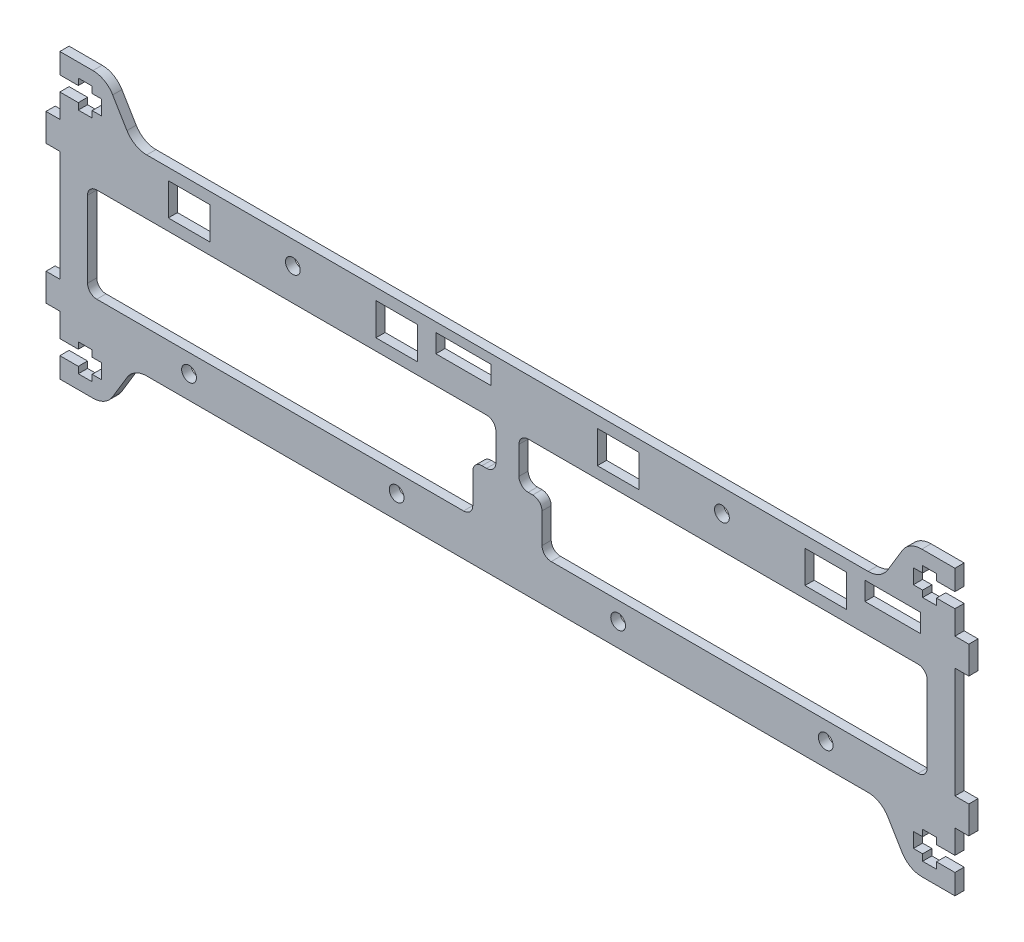
SolidWorks part; units mm, degrees
material "Thornel Mat VMA"
ref_plane "前视基准面" through (0, 0, 0) normal (0, 0, 1) x (1, 0, 0)
ref_plane "上视基准面" through (0, 0, 0) normal (0, 1, 0) x (1, 0, 0)
ref_plane "右视基准面" through (0, 0, 0) normal (1, 0, 0) x (0, 0, -1)
sketch "草图1" plane through (0, 0, 0) normal (0, 0, 1) x (1, 0, 0)
  line L0 (0, 37.9064) -> (0, -47.7397) construction
  line L5 (-108.9606, 0) -> (106.7668, 0) construction
  line L6 (-46.5, 17.25) -> (-46.5, -19.8871) construction
  line L57 (-91, 10.25) -> (-7.5, 10.25)
  line L58 (-91, 10.25) -> (-91, -10.25)
  line L59 (-91, -10.25) -> (-7.5, -10.25)
  line L60 (-7.5, 10.25) -> (-7.5, -10.25)
  line L61 (7.5, 10.25) -> (91, 10.25)
  line L62 (7.5, 10.25) -> (7.5, -10.25)
  line L63 (7.5, -10.25) -> (91, -10.25)
  line L64 (91, 10.25) -> (91, -10.25)
  line L80 (64, -19.25) -> (29, -19.25)
  line L81 (-97, 22.25) -> (97, 22.25)
  line L82 (-97, 22.25) -> (-97, -24.75)
  line L83 (-97, -24.75) -> (-64, -24.75)
  line L84 (97, 22.25) -> (97, -24.75)
  line L86 (-64, -24.75) -> (-64, -19.25)
  line L87 (-64, -19.25) -> (-29, -19.25)
  line L88 (-29, -24.75) -> (-29, -19.25)
  line L89 (29, -24.75) -> (29, -19.25)
  line L91 (64, -24.75) -> (64, -19.25)
  line L92 (-29, -24.75) -> (29, -24.75)
  line L93 (64, -24.75) -> (97, -24.75)
  circle A0 centre (-46.5, 17.25) radius 1.6
  circle A1 centre (-69, -14.25) radius 1.6
  circle A2 centre (-24, -14.25) radius 1.6
  circle A3 centre (69, -14.25) radius 1.6
  circle A4 centre (46.5, 17.25) radius 1.6
  circle A5 centre (24, -14.25) radius 1.6
  circle A6 centre (-69, -21.75) radius 1.6
  circle A7 centre (-24, -21.75) radius 1.6
  circle A8 centre (24, -21.75) radius 1.6
  circle A9 centre (69, -21.75) radius 1.6
  point P30 (0, 0)
  dimension "D1" = 3.2
  dimension "D2" = 45
  dimension "D3" = 31.5
  dimension "D4" = 5
  dimension "D5" = 28
  dimension "D8" = 7.5
  dimension "D6" = 48
  dimension "D7" = 7
  dimension "D9" = 3
  dimension "D10" = 6
  dimension "D11" = 9
  dimension "D12" = 5
  dimension "D15" = 4
  dimension "D16" = 15
extrude "凸台-拉伸1" add sketch "草图1" along normal blind 2
sketch "草图3" plane through (0, 0, 2) normal (0, 0, 1) x (1, 0, 0)
  line L1 (-7.5, 10.25) -> (-2.5, 10.25)
  line L2 (-7.5, 10.25) -> (-7.5, 0.25)
  line L3 (-7.5, 0.25) -> (-2.5, 0.25)
  line L4 (-2.5, 10.25) -> (-2.5, 0.25)
  line L5 (7.5, 10.25) -> (2.5, 10.25)
  line L6 (7.5, 10.25) -> (7.5, 0.25)
  line L7 (7.5, 0.25) -> (2.5, 0.25)
  line L8 (2.5, 10.25) -> (2.5, 0.25)
  dimension "D1" = 5
  dimension "D2" = 10
extrude "切除-拉伸2" cut sketch "草图3" against normal through all
sketch "草图4" plane through (0, 0, 0) normal (0, 0, -1) x (-1, 0, 0)
  line L0 (-97, 22.25) -> (97, 22.25) construction
  line L1 (-73.5, 19.75) -> (-64.5, 19.75)
  line L2 (-73.5, 19.75) -> (-73.5, 12.75)
  line L3 (-73.5, 12.75) -> (-64.5, 12.75)
  line L4 (-64.5, 19.75) -> (-64.5, 12.75)
  line L5 (0, 22.25) -> (0, -24.75) construction
  line L6 (-28.5, 19.75) -> (-19.5, 19.75)
  line L7 (-28.5, 19.75) -> (-28.5, 12.75)
  line L8 (-28.5, 12.75) -> (-19.5, 12.75)
  line L9 (-19.5, 19.75) -> (-19.5, 12.75)
  line L10 (29, -24.75) -> (-29, -24.75) construction
  line L11 (-46.5, 17.25) -> (-46.5, -22.9555) construction
  line L12 (28.5, 12.75) -> (19.5, 12.75)
  line L13 (19.5, 19.75) -> (19.5, 12.75)
  line L14 (28.5, 19.75) -> (19.5, 19.75)
  line L15 (28.5, 19.75) -> (28.5, 12.75)
  line L16 (73.5, 12.75) -> (64.5, 12.75)
  line L17 (64.5, 19.75) -> (64.5, 12.75)
  line L18 (73.5, 19.75) -> (64.5, 19.75)
  line L19 (73.5, 19.75) -> (73.5, 12.75)
  line L20 (-64, -24.75) -> (-97, -24.75) construction
  line L21 (-74, -24.75) -> (-97, -24.75)
  line L22 (-74, -24.75) -> (-74, -19.25)
  line L23 (-74, -19.25) -> (-97, -19.25)
  line L24 (-97, -24.75) -> (-97, -19.25)
  line L25 (-97, -24.75) -> (-97, 22.25) construction
  line L26 (97, -24.75) -> (64, -24.75) construction
  line L27 (74, -24.75) -> (97, -24.75)
  line L28 (74, -24.75) -> (74, -19.25)
  line L29 (74, -19.25) -> (97, -19.25)
  line L30 (97, -24.75) -> (97, -19.25)
  line L31 (97, 22.25) -> (97, -24.75) construction
  line L32 (-29, -19.25) -> (-64, -19.25) construction
  line L34 (-19, -24.75) -> (19, -24.75)
  line L35 (-19, -24.75) -> (-19, -19.25)
  line L36 (-19, -19.25) -> (19, -19.25)
  line L37 (19, -24.75) -> (19, -19.25)
  circle A0 centre (-46.5, 17.25) radius 1.6 construction
  circle A1 centre (-69, -21.75) radius 1.6 construction
  circle A2 centre (-24, -21.75) radius 1.6 construction
  dimension "D1" = 4.5
  dimension "D2" = 18
  dimension "D3" = 27
  dimension "D4" = 7
  dimension "D5" = 5
  dimension "D6" = 5
extrude "切除-拉伸3" cut sketch "草图4" against normal through all
sketch "草图5" plane through (0, 0, 0) normal (0, 0, -1) x (-1, 0, 0)
  line L0 (-97, 22.25) -> (97, 22.25) construction
  line L1 (-89.5, 20.25) -> (-77.5, 20.25)
  line L2 (-89.5, 20.25) -> (-89.5, 16.25)
  line L3 (-89.5, 16.25) -> (-77.5, 16.25)
  line L4 (-77.5, 20.25) -> (-77.5, 16.25)
  line L5 (3.5, 20.25) -> (15.5, 20.25)
  line L6 (3.5, 20.25) -> (3.5, 16.25)
  line L7 (3.5, 16.25) -> (15.5, 16.25)
  line L8 (15.5, 20.25) -> (15.5, 16.25)
  line L9 (-73.5, 19.75) -> (-73.5, 12.75) construction
  line L10 (19.5, 19.75) -> (19.5, 12.75) construction
  point P12 (16.5382, 19.75)
  dimension "D1" = 12
  dimension "D2" = 4
  dimension "D3" = 2
  dimension "D4" = 4
  dimension "D5" = 4
extrude "切除-拉伸4" cut sketch "草图5" against normal through all
fillet "圆角8" radius 2 12 edges at (91, -10.25, 1) (91, 10.25, 1) (-91, -10.25, 1) (-91, 10.25, 1) (-7.5, -10.25, 1) (7.5, -10.25, 1) (-7.5, 0.25, 1) (-2.5, 10.25, 1) (-2.5, 0.25, 1) (7.5, 0.25, 1) (2.5, 0.25, 1) (2.5, 10.25, 1)
fillet "圆角9" radius 2 16 edges at (-74, -19.25, 1) (-74, -24.75, 1) (-64, -24.75, 1) (-64, -19.25, 1) (-19, -19.25, 1) (-19, -24.75, 1) (-29, -24.75, 1) (-29, -19.25, 1) (19, -19.25, 1) (19, -24.75, 1) (29, -24.75, 1) (29, -19.25, 1) (64, -24.75, 1) (64, -19.25, 1) (74, -24.75, 1) (74, -19.25, 1)
sketch "草图7" plane through (0, 0, 0) normal (0, 0, -1) x (-1, 0, 0)
  line L0 (0, 46.7997) -> (0, -61.1375) construction
  line L2 (-97, 22.25) -> (-87, 22.25)
  line L3 (-97, 22.25) -> (-97, 32.25)
  line L4 (-97, 32.25) -> (-87, 32.25)
  line L5 (-87, 22.25) -> (-87, 32.25)
  line L6 (-97, -19.25) -> (-87, -19.25)
  line L7 (-97, -19.25) -> (-97, -29.25)
  line L8 (-97, -29.25) -> (-87, -29.25)
  line L9 (-87, -19.25) -> (-87, -29.25)
  line L10 (97, 22.25) -> (87, 22.25)
  line L11 (97, 22.25) -> (97, 32.25)
  line L12 (97, 32.25) -> (87, 32.25)
  line L13 (87, 22.25) -> (87, 32.25)
  line L14 (97, -19.25) -> (87, -19.25)
  line L15 (97, -19.25) -> (97, -29.25)
  line L16 (97, -29.25) -> (87, -29.25)
  line L17 (87, -19.25) -> (87, -29.25)
  dimension "D1" = 10
  dimension "D2" = 10
extrude "凸台-拉伸3" add sketch "草图7" against normal up to surface (2 mm away) up to face at (83.5, 18.25, 2)
sketch "草图8" plane through (0, 0, 0) normal (0, 0, -1) x (-1, 0, 0)
  line L0 (-87, 32.25) -> (-81, 22.25)
  line L2 (-81, 22.25) -> (-87, 22.25)
  line L3 (-87, 22.25) -> (-87, 32.25)
  line L4 (87, 32.25) -> (81, 22.25)
  line L5 (81, 22.25) -> (87, 22.25)
  line L6 (87, 22.25) -> (87, 32.25)
  line L7 (-87, -29.25) -> (-81, -19.25)
  line L9 (-81, -19.25) -> (-87, -19.25)
  line L10 (-87, -19.25) -> (-87, -29.25)
  line L11 (87, -29.25) -> (81, -19.25)
  line L13 (81, -19.25) -> (87, -19.25)
  line L14 (87, -29.25) -> (87, -19.25)
  line L15 (-97, 1.5) -> (110.1882, 1.5) construction
  line L16 (-97, -29.25) -> (-97, 32.25) construction
  line L17 (0, 22.25) -> (0, -25.9859) construction
  line L18 (-87, 22.25) -> (87, 22.25) construction
  line L20 (-100, 19.5) -> (-97, 19.5)
  line L21 (-100, 19.5) -> (-100, 13.5)
  line L22 (-100, 13.5) -> (-97, 13.5)
  line L23 (-97, 19.5) -> (-97, 13.5)
  line L24 (-100, -10.5) -> (-97, -10.5)
  line L25 (-100, -10.5) -> (-100, -16.5)
  line L26 (-100, -16.5) -> (-97, -16.5)
  line L27 (-97, -10.5) -> (-97, -16.5)
  line L32 (100, -16.5) -> (97, -16.5)
  line L33 (97, -10.5) -> (97, -16.5)
  line L34 (100, -10.5) -> (97, -10.5)
  line L35 (100, -10.5) -> (100, -16.5)
  line L36 (100, 13.5) -> (97, 13.5)
  line L37 (97, 19.5) -> (97, 13.5)
  line L38 (100, 19.5) -> (97, 19.5)
  line L39 (100, 19.5) -> (100, 13.5)
  point P37 (-100, 16.5)
  point P38 (-100, -13.5)
  point P39 (0, 0)
  dimension "D1" = 6
  dimension "D2" = 6
  dimension "D3" = 30
  dimension "D4" = 3
sketch "草图9" plane through (0, 0, 0) normal (0, 0, -1) x (-1, 0, 0)
  line L0 (-81, -19.25) -> (-87, -19.25) construction
  line L1 (-80.6647, -19.25) -> (81.9042, -19.25)
  line L2 (-80.6647, -19.25) -> (-80.6647, -40.5339)
  line L3 (-80.6647, -40.5339) -> (81.9042, -40.5339)
  line L4 (81.9042, -19.25) -> (81.9042, -40.5339)
extrude "切除-拉伸5" cut sketch "草图9" against normal through all
extrude "凸台-拉伸4" add sketch "草图8" against normal up to surface (2 mm away) up to face at (0, 1.5, 2)
sketch "草图10" plane through (0, 0, 0) normal (0, 0, -1) x (-1, 0, 0)
  line L0 (-97, -29.25) -> (-97, -16.5) construction
  line L1 (-97, 27.85) -> (-93, 27.85)
  line L2 (-97, 27.85) -> (-97, 24.65)
  line L3 (-97, 24.65) -> (-93, 24.65)
  line L4 (-88, 27.85) -> (-88, 24.65)
  line L5 (0, 35.4071) -> (0, -42.2121) construction
  line L6 (-93, 29.25) -> (-90, 29.25)
  line L7 (-93, 29.25) -> (-93, 27.85)
  line L8 (-93, 23.25) -> (-90, 23.25)
  line L9 (-90, 29.25) -> (-90, 27.85)
  line L10 (-108.4136, 0) -> (106.0624, 0) construction
  line L11 (-97, 26.25) -> (-88, 26.25) construction
  line L12 (-87, 32.25) -> (-97, 32.25) construction
  line L13 (-93, 24.65) -> (-93, 23.25)
  line L14 (-90, 27.85) -> (-88, 27.85)
  line L15 (-90, 24.65) -> (-90, 23.25)
  line L16 (-90, 24.65) -> (-88, 24.65)
  line L29 (-97, 1.5) -> (-56.3273, 1.5) construction
  line L30 (-97, -24.85) -> (-93, -24.85)
  line L31 (-93, -26.25) -> (-93, -24.85)
  line L32 (-93, -26.25) -> (-90, -26.25)
  line L33 (-90, -26.25) -> (-90, -24.85)
  line L34 (-90, -24.85) -> (-88, -24.85)
  line L35 (-88, -24.85) -> (-88, -21.65)
  line L36 (-90, -21.65) -> (-88, -21.65)
  line L37 (-90, -21.65) -> (-90, -20.25)
  line L38 (-93, -20.25) -> (-90, -20.25)
  line L39 (-93, -21.65) -> (-93, -20.25)
  line L40 (-97, -21.65) -> (-93, -21.65)
  line L41 (-97, -24.85) -> (-97, -21.65)
  line L42 (97, -24.85) -> (97, -21.65)
  line L43 (97, -21.65) -> (93, -21.65)
  line L44 (93, -21.65) -> (93, -20.25)
  line L45 (93, -20.25) -> (90, -20.25)
  line L46 (90, -21.65) -> (90, -20.25)
  line L47 (90, -21.65) -> (88, -21.65)
  line L48 (88, -24.85) -> (88, -21.65)
  line L49 (90, -24.85) -> (88, -24.85)
  line L50 (90, -26.25) -> (90, -24.85)
  line L51 (93, -26.25) -> (90, -26.25)
  line L52 (93, -26.25) -> (93, -24.85)
  line L53 (97, -24.85) -> (93, -24.85)
  line L54 (97, 27.85) -> (93, 27.85)
  line L55 (93, 29.25) -> (93, 27.85)
  line L56 (93, 29.25) -> (90, 29.25)
  line L57 (90, 29.25) -> (90, 27.85)
  line L58 (90, 27.85) -> (88, 27.85)
  line L59 (88, 27.85) -> (88, 24.65)
  line L60 (90, 24.65) -> (88, 24.65)
  line L61 (90, 24.65) -> (90, 23.25)
  line L62 (93, 23.25) -> (90, 23.25)
  line L63 (93, 24.65) -> (93, 23.25)
  line L64 (97, 24.65) -> (93, 24.65)
  line L65 (97, 27.85) -> (97, 24.65)
  line L66 (-97, -10.5) -> (-97, 13.5) construction
  point P61 (-97, 1.5)
  dimension "D1" = 3.2
  dimension "D2" = 6
  dimension "D3" = 4
  dimension "D4" = 9
  dimension "D5" = 3
  dimension "D6" = 6
extrude "切除-拉伸6" cut sketch "草图10" against normal through all
fillet "圆角10" radius 5 8 edges at (-87, -29.25, 1) (-81, -19.25, 1) (81, -19.25, 1) (87, -29.25, 1) (87, 32.25, 1) (81, 22.25, 1) (-87, 32.25, 1) (-81, 22.25, 1)
